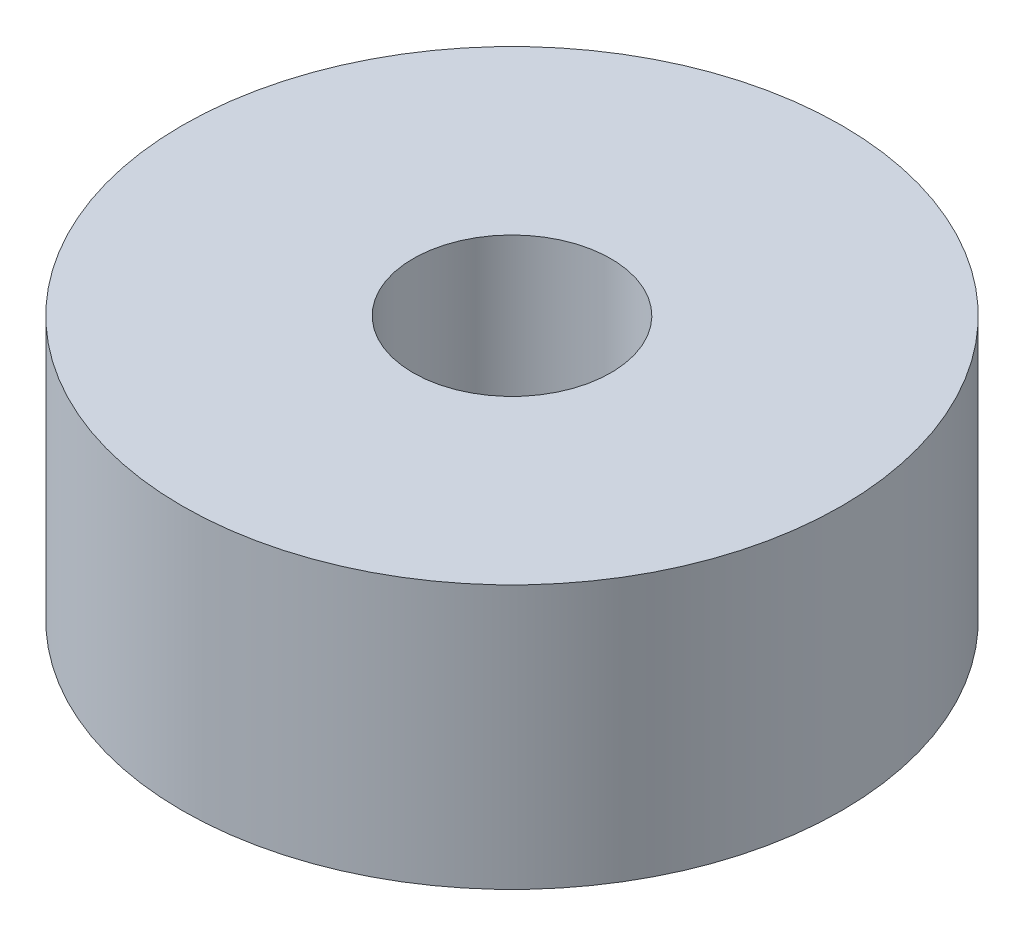
SolidWorks part; units mm, degrees
ref_plane "前视基准面" through (0, 0, 0) normal (0, 0, 1) x (1, 0, 0)
ref_plane "上视基准面" through (0, 0, 0) normal (0, 1, 0) x (1, 0, 0)
ref_plane "右视基准面" through (0, 0, 0) normal (1, 0, 0) x (0, 0, -1)
sketch "草图1" plane through (0, 0, 0) normal (0, 1, 0) x (1, 0, 0)
  circle A0 centre (0, 0) radius 1.5
  circle A1 centre (0, 0) radius 5
  dimension "D1" = 3
  dimension "D2" = 10
extrude "凸台-拉伸1" add sketch "草图1" along normal mid plane 4
